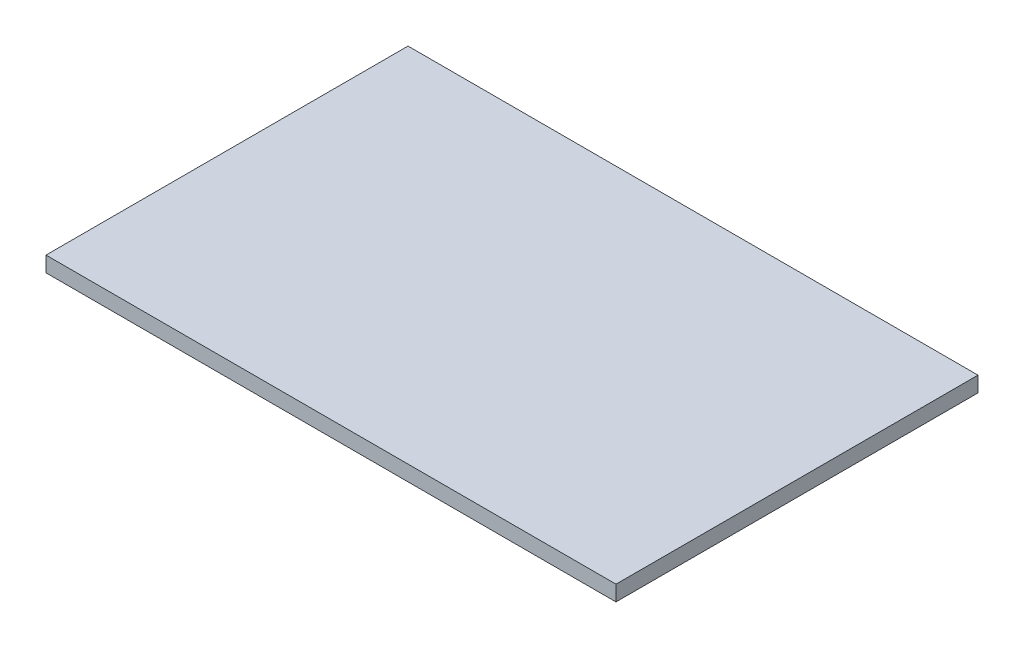
SolidWorks part; units mm, degrees
ref_plane "Front Plane" through (0, 0, 0) normal (0, 0, 1) x (1, 0, 0)
ref_plane "Top Plane" through (0, 0, 0) normal (0, 1, 0) x (1, 0, 0)
ref_plane "Right Plane" through (0, 0, 0) normal (1, 0, 0) x (0, 0, -1)
sketch "Sketch2" plane through (0, 0, 0) normal (0, 1, 0) x (1, 0, 0)
  line L1 (370, -235) -> (-370, -235)
  line L2 (370, -235) -> (370, 235)
  line L3 (370, 235) -> (-370, 235)
  line L4 (-370, -235) -> (-370, 235)
  line L5 (370, -235) -> (-370, 235) construction
  line L6 (370, 235) -> (-370, -235) construction
  point P0 (0, 0)
  dimension "D1" = 470
  dimension "D2" = 740
extrude "Boss-Extrude1" add sketch "Sketch2" along normal blind 20
